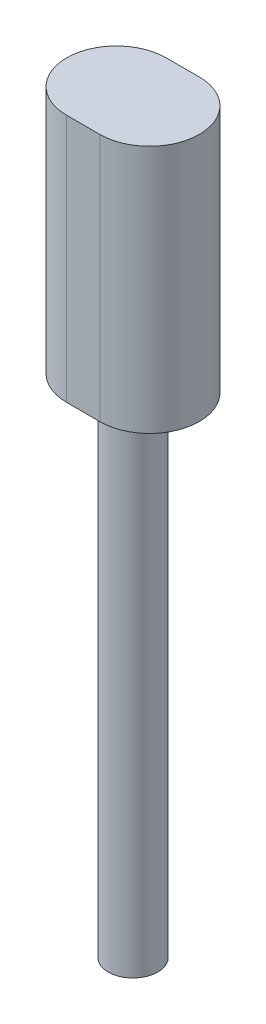
SolidWorks part; units mm, degrees
ref_plane "Front" through (0, 0, 0) normal (0, 0, 1) x (1, 0, 0)
ref_plane "Top" through (0, 0, 0) normal (0, 1, 0) x (1, 0, 0)
ref_plane "Right" through (0, 0, 0) normal (1, 0, 0) x (0, 0, -1)
sketch "草图2" plane through (0, 0, 0) normal (0, 1, 0) x (1, 0, 0)
  line L0 (-1, 0) -> (1, 0) construction
  line L1 (-1, 3) -> (1, 3)
  line L2 (-1, -3) -> (1, -3)
  arc A0 (-1, 3) -> (-1, -3) centre (-1, 0) ccw
  arc A1 (1, -3) -> (1, 3) centre (1, 0) ccw
  point P2 (0, 0)
extrude "凸台-拉伸1" add sketch "草图2" along normal blind 15
sketch "草图3" plane through (0, 0, 0) normal (0, 1, 0) x (1, 0, 0)
  circle A0 centre (0, 0) radius 1.5
extrude "凸台-拉伸2" add sketch "草图3" against normal blind 30
